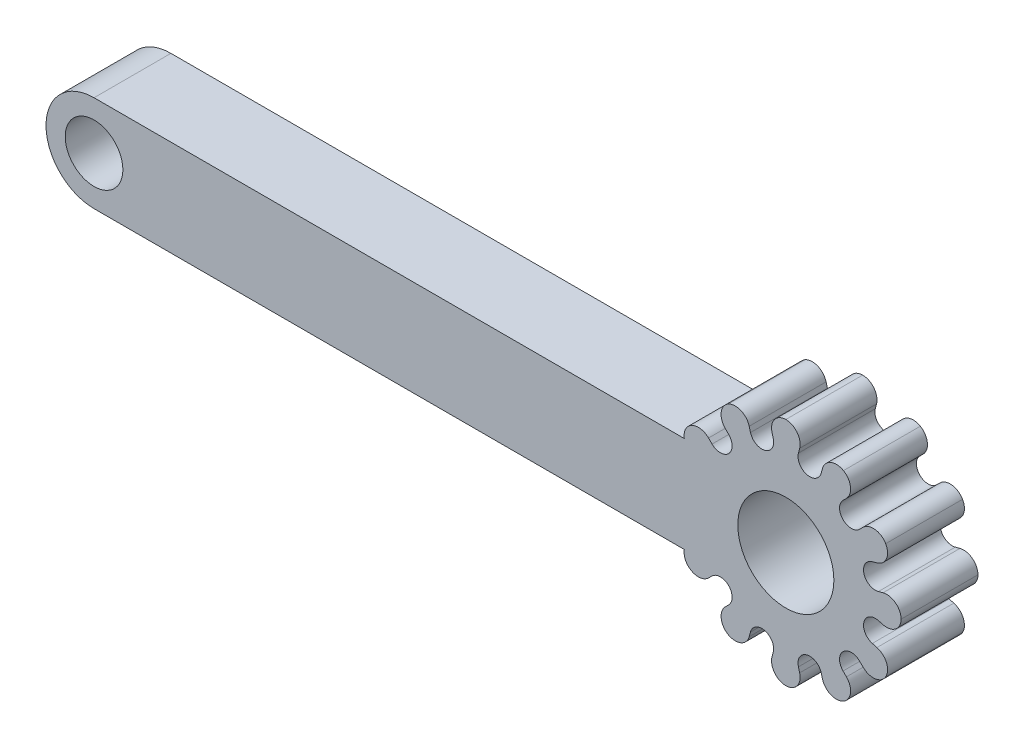
SolidWorks part; units mm, degrees
ref_plane "Front Plane" through (0, 0, 0) normal (0, 0, 1) x (1, 0, 0)
ref_plane "Top Plane" through (0, 0, 0) normal (0, 1, 0) x (1, 0, 0)
ref_plane "Right Plane" through (0, 0, 0) normal (1, 0, 0) x (0, 0, -1)
sketch "Sketch1" plane through (0, 0, 0) normal (0, 0, 1) x (1, 0, 0)
  line L0 (-18, 0) -> (18, 0) construction
  line L1 (-18, 2.5) -> (-18, -2.5) construction
  line L2 (-18, 2.5) -> (12.5456, 2.5)
  line L3 (-18, -2.5) -> (12.5456, -2.5)
  circle A0 centre (-18, 0) radius 1.5
  arc A1 (-18, 2.5) -> (-18, -2.5) centre (-18, 0) ccw
  arc A2 (12.5456, -2.5) -> (12.5456, 2.5) centre (18, 0) ccw
  point P4 (0, 0)
  dimension "D2" = 3
  dimension "D3" = 5
  dimension "D4" = 12
  dimension "D1" = 36
extrude "Boss-Extrude1" add sketch "Sketch1" along normal blind 4
sketch "Sketch2" plane through (0, 0, 4) normal (0, 0, 1) x (1, 0, 0)
  line L0 (18, 6) -> (18, -6) construction
  line L1 (18, 0) -> (21, 5.1962) construction
  line L2 (18, 0) -> (19.2475, 4.6558) construction
  line L3 (18.72, 5.06) -> (18.6545, 4.81)
  line L4 (18.6545, 4.81) -> (19.8405, 4.5015) construction
  line L5 (19.9065, 4.7421) -> (19.8405, 4.5015)
  arc A0 (12.5456, -2.5) -> (12.5456, 2.5) centre (18, 0) ccw construction
  arc A1 (18, 6) -> (18.72, 5.06) centre (17.9945, 5.25) cw
  arc A2 (18.6545, 4.81) -> (19.8405, 4.5015) centre (19.2475, 4.6558) ccw
  arc A3 (21, 5.1962) -> (19.9065, 4.7421) centre (20.6299, 4.5437) ccw
  arc A6 (18, 6) -> (21, 5.1962) centre (18.3533, 1.3187) cw
  dimension "D6" = 0.75
  dimension "D1" = 30
  dimension "D2" = 4.82
  dimension "D3" = 15
  dimension "D4" = 0.94
  dimension "D5" = 0.72
  dimension "D8" = 0.25
extrude "Cut-Extrude2" cut sketch "Sketch2" against normal through all
pattern_circular "CirPattern1" count 12 over 360 about axis through (18, 0, 0) along (0, 0, 1) of "Cut-Extrude2"
sketch "Sketch3" plane through (0, 0, 4) normal (0, 0, 1) x (1, 0, 0)
  line L0 (12.5062, 2.5) -> (-18, 2.5) construction
  line L1 (10.4382, 2.5) -> (20.0783, 2.5)
  line L2 (10.4382, 2.5) -> (10.4382, -2.5)
  line L3 (10.4382, -2.5) -> (20.0783, -2.5)
  line L4 (20.0783, 2.5) -> (20.0783, -2.5)
  line L5 (-18, -2.5) -> (12.5062, -2.5) construction
extrude "Boss-Extrude6" add sketch "Sketch3" against normal blind 4
sketch "Sketch4" plane through (0, 0, 4) normal (0, 0, 1) x (1, 0, 0)
  line L0 (18, 6) -> (18, -6) construction
  circle A0 centre (18, 0) radius 2.5
  dimension "D1" = 5
extrude "Cut-Extrude3" cut sketch "Sketch4" against normal through all
